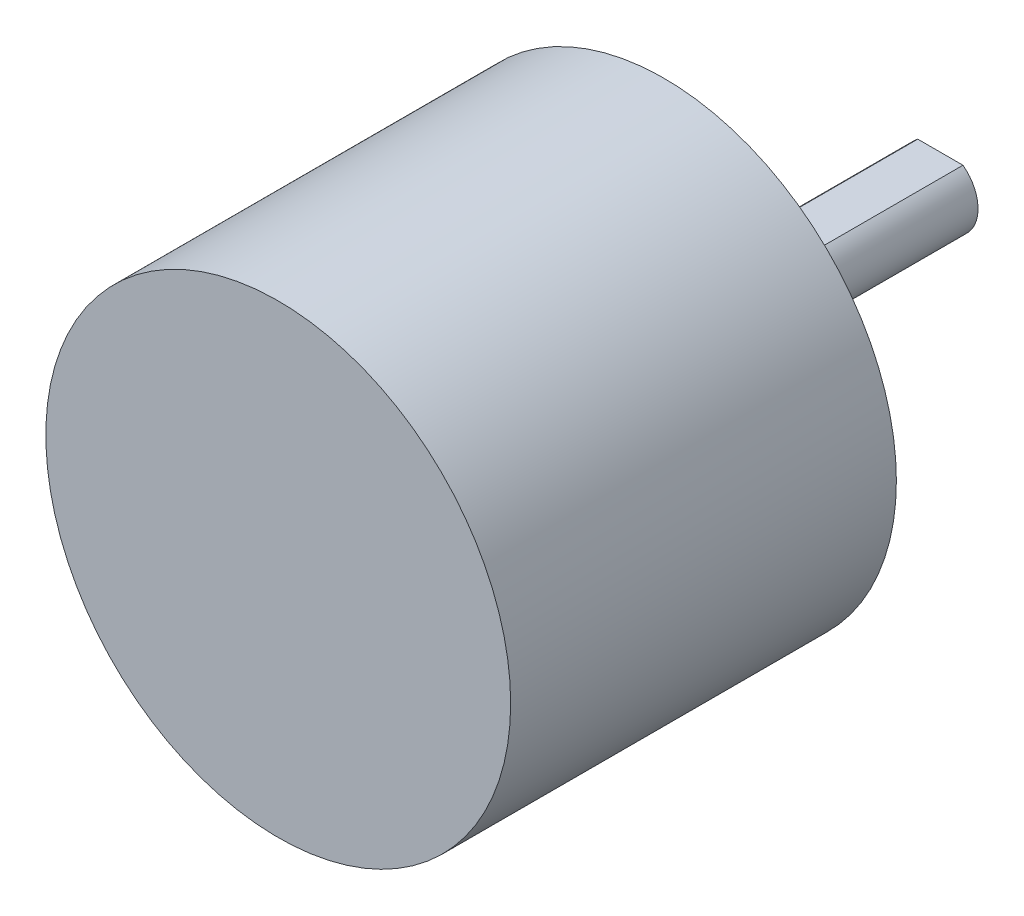
SolidWorks part; units mm, degrees
ref_plane "Plan de face" through (0, 0, 0) normal (0, 0, 1) x (1, 0, 0)
ref_plane "Plan de dessus" through (0, 0, 0) normal (0, 1, 0) x (1, 0, 0)
ref_plane "Plan de droite" through (0, 0, 0) normal (1, 0, 0) x (0, 0, -1)
sketch "Esquisse1" plane through (0, 0, 0) normal (0, 0, 1) x (1, 0, 0)
  circle A0 centre (0, 0) radius 18.5
  dimension "D1" = 37
extrude "Boss.-Extru.1" add sketch "Esquisse1" along normal blind 30.7
sketch "Esquisse2" plane through (0, 0, 0) normal (0, 0, -1) x (-1, 0, 0)
  circle A0 centre (0, 0) radius 5
  dimension "D1" = 10
extrude "Boss.-Extru.2" add sketch "Esquisse2" along normal blind 6 contours A0
sketch "Esquisse3" plane through (0, 0, -6) normal (0, 0, -1) x (-1, 0, 0)
  circle A0 centre (0, 0) radius 3
  dimension "D1" = 6
extrude "Boss.-Extru.3" add sketch "Esquisse3" along normal blind 16
sketch "Esquisse4" plane through (0, 0, -22) normal (0, 0, -1) x (-1, 0, 0)
  line L1 (-1.8, 2.4) -> (1.8, 2.4)
  circle A0 centre (0, 0) radius 3 construction
  circle A1 centre (0, 0) radius 3 construction
extrude "Enlèv. mat.-Extru.2" cut sketch "Esquisse4" against normal blind 16 and the other way through all
